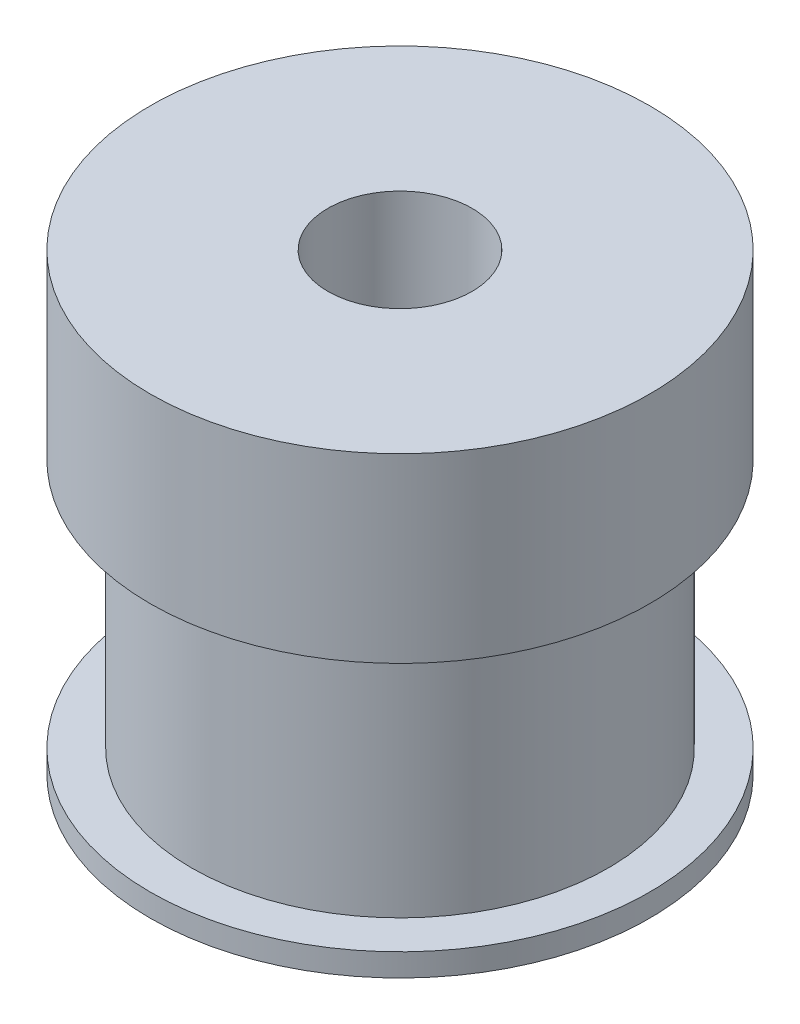
SolidWorks part; units mm, degrees
ref_plane "Спереди" through (0, 0, 0) normal (0, 0, 1) x (1, 0, 0)
ref_plane "Сверху" through (0, 0, 0) normal (0, 1, 0) x (1, 0, 0)
ref_plane "Справа" through (0, 0, 0) normal (1, 0, 0) x (0, 0, -1)
sketch "Эскиз1" plane through (0, 0, 0) normal (0, 1, 0) x (1, 0, 0)
  circle A0 centre (0, 0) radius 11
  dimension "D1" = 22
extrude "Бобышка-Вытянуть1" add sketch "Эскиз1" along normal blind 1
sketch "Эскиз2" plane through (0, 1, 0) normal (0, 1, 0) x (1, 0, 0)
  circle A0 centre (0, 0) radius 9.17
  dimension "D1" = 18.34
extrude "Бобышка-Вытянуть2" add sketch "Эскиз2" along normal blind 11
sketch "Эскиз3" plane through (0, 12, 0) normal (0, 1, 0) x (1, 0, 0)
  circle A0 centre (0, 0) radius 11
  dimension "D1" = 22
extrude "Бобышка-Вытянуть3" add sketch "Эскиз3" along normal blind 8
sketch "Эскиз4" plane through (0, 20, 0) normal (0, 1, 0) x (1, 0, 0)
  circle A0 centre (0, 0) radius 3.175
  dimension "D1" = 6.35
extrude "Вырез-Вытянуть1" cut sketch "Эскиз4" against normal through all
